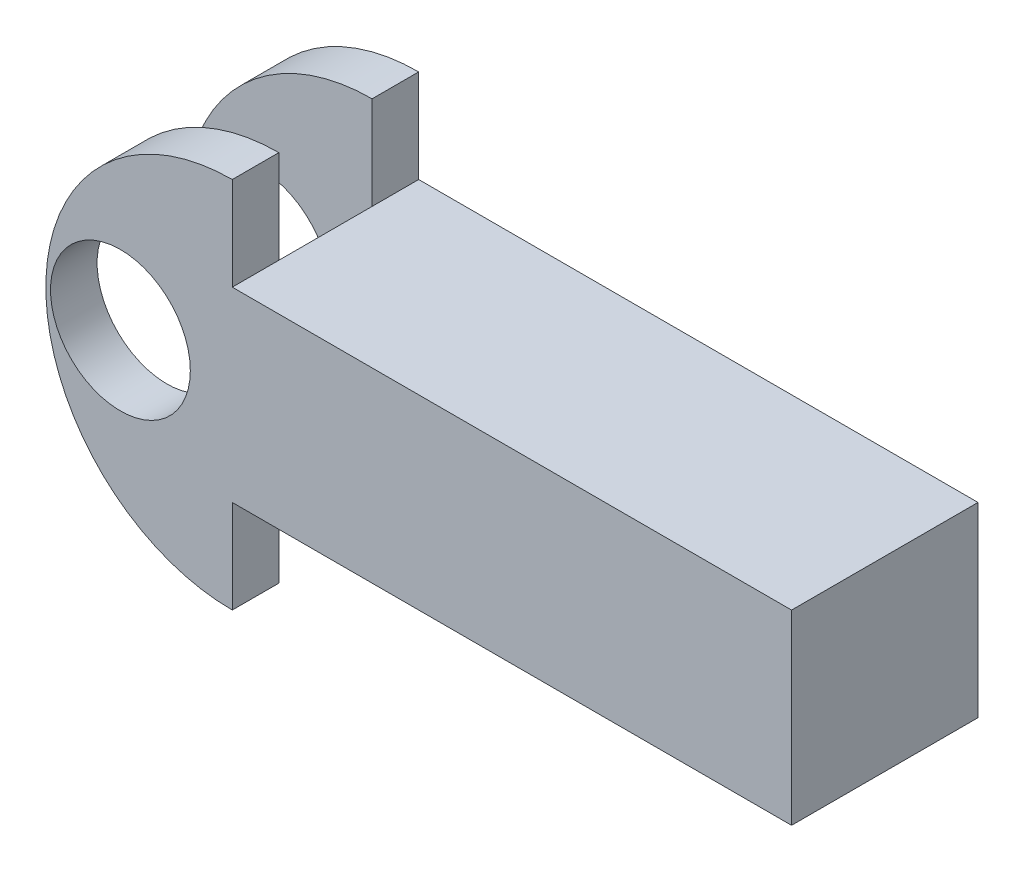
SolidWorks part; units mm, degrees
ref_plane "前视基准面" through (0, 0, 0) normal (0, 0, 1) x (1, 0, 0)
ref_plane "上视基准面" through (0, 0, 0) normal (0, 1, 0) x (1, 0, 0)
ref_plane "右视基准面" through (0, 0, 0) normal (1, 0, 0) x (0, 0, -1)
other "Configuration Table"
sketch "草图1" plane through (0, 0, 0) normal (0, 0, 1) x (1, 0, 0)
  line L1 (-30, -10) -> (30, -10)
  line L2 (-30, -10) -> (-30, 10)
  line L3 (-30, 10) -> (30, 10)
  line L4 (30, -10) -> (30, 10)
  line L5 (-30, -10) -> (30, 10) construction
  line L6 (-30, 10) -> (30, -10) construction
  point P0 (0, 0)
  dimension "D1" = 60
  dimension "D2" = 20
extrude "凸台-拉伸1" add sketch "草图1" along normal mid plane 20
ref_plane "基准面1" through (0, 0, -5) normal (0, 0, 1) x (1, 0, 0)
sketch "草图2" plane through (0, 0, -5) normal (0, 0, 1) x (1, 0, 0)
  line L0 (-30, 10) -> (-30, -10) construction
  line L1 (-30, 20) -> (-30, -20)
  arc A0 (-30, 20) -> (-30, -20) centre (-30, 0) ccw
  circle A1 centre (-42, 0) radius 7.5
  dimension "D1" = 40
  dimension "D2" = 12
extrude "凸台-拉伸2" add sketch "草图2" against normal blind 5
mirror "镜向4" about plane through (0, 0, 0) normal (0, 0, 1) of "凸台-拉伸2"
sketch "草图3" plane through (0, 0, 10) normal (0, 0, 1) x (1, 0, 0)
  circle A0 centre (-42, 0) radius 7.5
